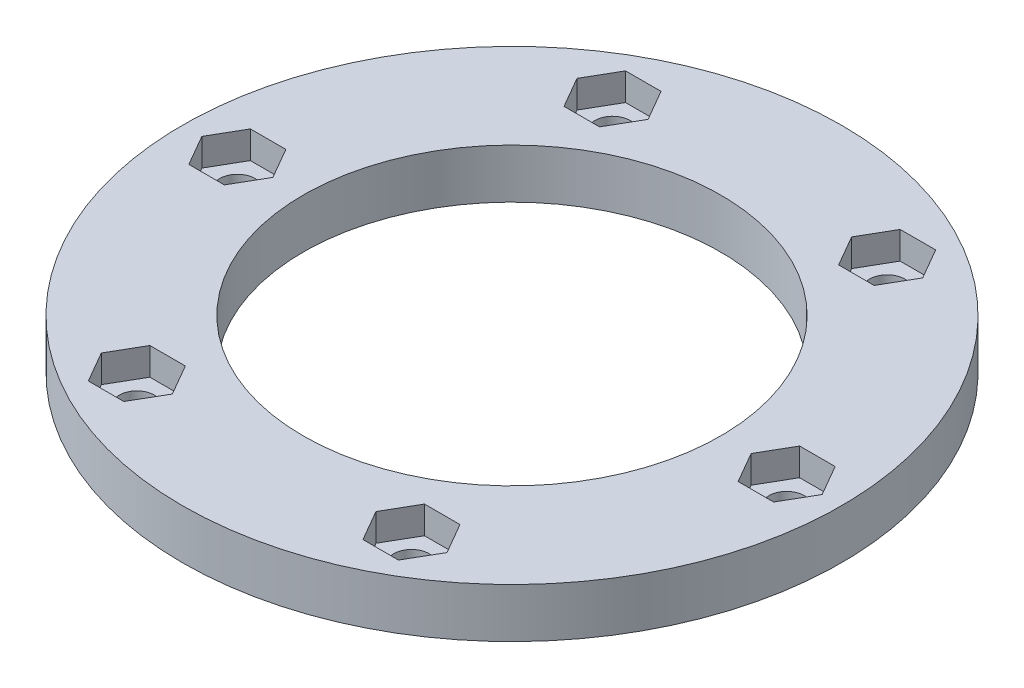
SolidWorks part; units mm, degrees
ref_plane "Front Plane" through (0, 0, 0) normal (0, 0, 1) x (1, 0, 0)
ref_plane "Top Plane" through (0, 0, 0) normal (0, 1, 0) x (1, 0, 0)
ref_plane "Right Plane" through (0, 0, 0) normal (1, 0, 0) x (0, 0, -1)
sketch "Sketch1" plane through (0, 0, 0) normal (0, 1, 0) x (1, 0, 0)
  circle A0 centre (0, 0) radius 30
  circle A1 centre (0, 0) radius 19
  circle A2 centre (25, 0) radius 1.6
  circle A3 centre (12.5, -21.6506) radius 1.6
  circle A4 centre (-12.5, -21.6506) radius 1.6
  circle A5 centre (-25, 0) radius 1.6
  circle A6 centre (-12.5, 21.6506) radius 1.6
  circle A7 centre (12.5, 21.6506) radius 1.6
  point P7 (0, 0)
  point P18 (0, 0)
  dimension "D1" = 60
  dimension "D2" = 38
  dimension "D3" = 3.2
  dimension "D4" = 25
  dimension "D5" = 6
extrude "Boss-Extrude1" add sketch "Sketch1" along normal blind 2
sketch "Sketch2" plane through (0, 2, 0) normal (0, 1, 0) x (1, 0, 0)
  line L0 (15.7332, -21.6506) -> (14.1166, -18.8506)
  line L1 (26.6166, -2.8) -> (28.2332, 0)
  line L2 (28.2332, 0) -> (26.6166, 2.8)
  line L3 (26.6166, 2.8) -> (23.3834, 2.8)
  line L4 (23.3834, 2.8) -> (21.7668, 0)
  line L5 (21.7668, 0) -> (23.3834, -2.8)
  line L6 (23.3834, -2.8) -> (26.6166, -2.8)
  line L7 (14.1166, -24.4506) -> (15.7332, -21.6506)
  line L8 (10.8834, -24.4506) -> (14.1166, -24.4506)
  line L9 (9.2668, -21.6506) -> (10.8834, -24.4506)
  line L10 (10.8834, -18.8506) -> (9.2668, -21.6506)
  line L11 (14.1166, -18.8506) -> (10.8834, -18.8506)
  line L12 (-10.8834, -24.4506) -> (-9.2668, -21.6506)
  line L13 (-14.1166, -24.4506) -> (-10.8834, -24.4506)
  line L14 (-15.7332, -21.6506) -> (-14.1166, -24.4506)
  line L15 (-14.1166, -18.8506) -> (-15.7332, -21.6506)
  line L16 (-10.8834, -18.8506) -> (-14.1166, -18.8506)
  line L17 (-9.2668, -21.6506) -> (-10.8834, -18.8506)
  line L18 (-26.6166, -2.8) -> (-23.3834, -2.8)
  line L19 (-28.2332, 0) -> (-26.6166, -2.8)
  line L20 (-26.6166, 2.8) -> (-28.2332, 0)
  line L21 (-23.3834, 2.8) -> (-26.6166, 2.8)
  line L22 (-21.7668, 0) -> (-23.3834, 2.8)
  line L23 (-23.3834, -2.8) -> (-21.7668, 0)
  line L24 (-15.7332, 21.6506) -> (-14.1166, 18.8506)
  line L25 (-14.1166, 24.4506) -> (-15.7332, 21.6506)
  line L26 (-10.8834, 24.4506) -> (-14.1166, 24.4506)
  line L27 (-9.2668, 21.6506) -> (-10.8834, 24.4506)
  line L28 (-10.8834, 18.8506) -> (-9.2668, 21.6506)
  line L29 (-14.1166, 18.8506) -> (-10.8834, 18.8506)
  line L30 (10.8834, 24.4506) -> (9.2668, 21.6506)
  line L31 (14.1166, 24.4506) -> (10.8834, 24.4506)
  line L32 (15.7332, 21.6506) -> (14.1166, 24.4506)
  line L33 (14.1166, 18.8506) -> (15.7332, 21.6506)
  line L34 (10.8834, 18.8506) -> (14.1166, 18.8506)
  line L35 (9.2668, 21.6506) -> (10.8834, 18.8506)
  circle A0 centre (25, 0) radius 2.8 construction
  circle A1 centre (0, 0) radius 19 construction
  circle A2 centre (0, 0) radius 30 construction
  circle A3 centre (0, 0) radius 19
  circle A4 centre (0, 0) radius 30
  point P11 (0, 0)
  point P42 (0, 0)
  dimension "D1" = 5.6
  dimension "D2" = 6
extrude "Boss-Extrude2" add sketch "Sketch2" along normal blind 2.5
